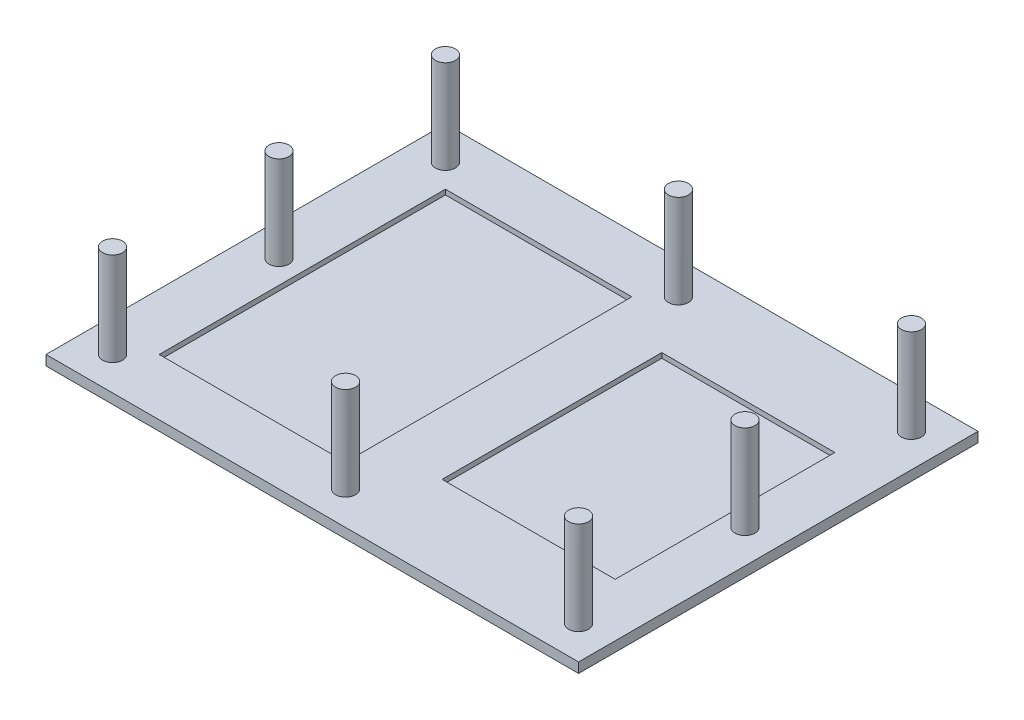
SolidWorks part; units mm, degrees
ref_plane "Front Plane" through (0, 0, 0) normal (0, 0, 1) x (1, 0, 0)
ref_plane "Top Plane" through (0, 0, 0) normal (0, 1, 0) x (1, 0, 0)
ref_plane "Right Plane" through (0, 0, 0) normal (1, 0, 0) x (0, 0, -1)
sketch "Sketch1" plane through (0, 0, 0) normal (0, 1, 0) x (1, 0, 0)
  line L1 (-80, -60) -> (80, -60)
  line L2 (-80, -60) -> (-80, 60)
  line L3 (-80, 60) -> (80, 60)
  line L4 (80, -60) -> (80, 60)
  line L5 (-80, -60) -> (80, 60) construction
  line L6 (-80, 60) -> (80, -60) construction
  point P0 (0, 0)
  dimension "D1" = 120
  dimension "D2" = 160
extrude "Boss-Extrude1" add sketch "Sketch1" along normal blind 3
sketch "Sketch2" plane through (0, 3, 0) normal (0, 1, 0) x (1, 0, 0)
  line L0 (0, 60) -> (0, 50) construction
  line L1 (80, 60) -> (-80, 60) construction
  line L2 (-80, -60) -> (80, -60) construction
  line L3 (80, 0) -> (70, 0) construction
  line L4 (80, -60) -> (80, 60) construction
  line L5 (-80, 0) -> (-70, 0) construction
  line L6 (-80, 60) -> (-80, -60) construction
  line L7 (-80, 60) -> (-70, 60) construction
  line L8 (-70, 60) -> (-70, 50) construction
  line L9 (-80, -60) -> (-70, -60) construction
  line L10 (-70, -60) -> (-70, -50) construction
  line L11 (80, 60) -> (70, 60) construction
  line L12 (70, 60) -> (70, 50) construction
  line L13 (80, -60) -> (70, -60) construction
  line L14 (70, -60) -> (70, -50) construction
  line L15 (0, -60) -> (0, -50) construction
  circle A0 centre (-70, 50) radius 3
  circle A1 centre (0, 50) radius 3
  circle A2 centre (70, 50) radius 3
  circle A3 centre (-70, 0) radius 3
  circle A4 centre (70, 0) radius 3
  circle A5 centre (-70, -50) radius 3
  circle A6 centre (0, -50) radius 3
  circle A7 centre (70, -50) radius 3
  dimension "D13" = 6
  dimension "D14" = 6
  dimension "D15" = 6
  dimension "D16" = 6
  dimension "D17" = 6
  dimension "D18" = 6
  dimension "D19" = 6
  dimension "D20" = 6
  dimension "D1" = 10
  dimension "D2" = 10
  dimension "D3" = 10
  dimension "D4" = 10
  dimension "D5" = 10
  dimension "D6" = 10
  dimension "D7" = 10
  dimension "D8" = 10
  dimension "D9" = 10
  dimension "D10" = 10
  dimension "D11" = 10
  dimension "D12" = 10
extrude "Boss-Extrude2" add sketch "Sketch2" along normal blind 28
sketch "Sketch3" plane through (0, 3, 0) normal (0, 1, 0) x (1, 0, 0)
  line L0 (80, 60) -> (-80, 60) construction
  line L1 (-63, -43) -> (-7, -43)
  line L2 (-63, -43) -> (-63, 43)
  line L3 (-63, 43) -> (-7, 43)
  line L4 (-7, -43) -> (-7, 43)
  line L6 (-80, 60) -> (-80, -60) construction
  dimension "D1" = 86
  dimension "D2" = 56
  dimension "D3" = 17
  dimension "D4" = 17
extrude "Cut-Extrude1" cut sketch "Sketch3" against normal blind 1.5 contours L2 L3 L4 L1
sketch "Sketch5" plane through (0, 3, 0) normal (0, 1, 0) x (1, 0, 0)
  line L0 (80, -60) -> (80, 60) construction
  line L1 (12, 33) -> (64, 33)
  line L2 (12, 33) -> (12, -33)
  line L3 (12, -33) -> (64, -33)
  line L4 (64, 33) -> (64, -33)
  line L5 (80, 60) -> (-80, 60) construction
  dimension "D1" = 52
  dimension "D2" = 66
  dimension "D3" = 16
  dimension "D4" = 27
extrude "Cut-Extrude2" cut sketch "Sketch5" against normal blind 1.5
